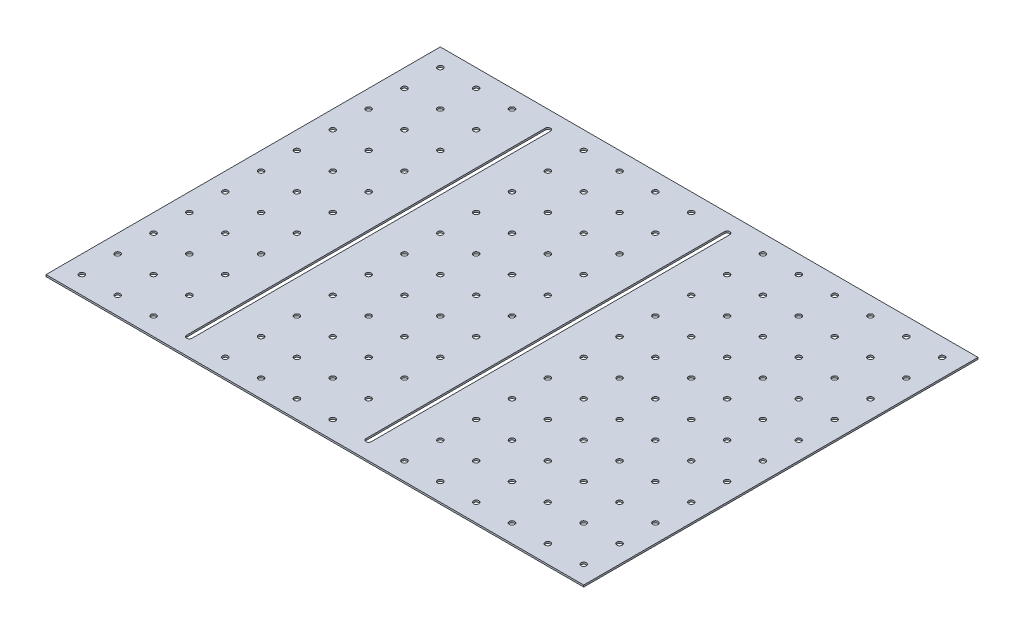
SolidWorks part; units mm, degrees
ref_plane "Front Plane" through (0, 0, 0) normal (0, 0, 1) x (1, 0, 0)
ref_plane "Top Plane" through (0, 0, 0) normal (0, 1, 0) x (1, 0, 0)
ref_plane "Right Plane" through (0, 0, 0) normal (1, 0, 0) x (0, 0, -1)
sketch "Sketch1" plane through (0, 0, 0) normal (0, 1, 0) x (1, 0, 0)
  line L1 (0, 0) -> (-300, 0)
  line L2 (0, 0) -> (0, 220)
  line L3 (0, 220) -> (-300, 220)
  line L4 (-300, 0) -> (-300, 220)
extrude "Boss-Extrude1" add sketch "Sketch1" along normal blind 1
sketch "Sketch2" plane through (0, 1, 0) normal (0, 1, 0) x (1, 0, 0)
  line L0 (-300, 220) -> (-300, 0) construction
  line L1 (0, 220) -> (-300, 220) construction
  line L2 (-280, 220) -> (-280, 0) construction
  line L3 (-300, 0) -> (0, 0) construction
  line L4 (-300, 200) -> (0, 200) construction
  line L5 (0, 0) -> (0, 220) construction
  line L6 (-280, 200) -> (-280, -20) construction
  line L7 (-280, 180) -> (-280, -40) construction
  line L8 (-280, 160) -> (-280, -60) construction
  line L9 (-280, 140) -> (-280, -80) construction
  line L10 (-280, 120) -> (-280, -100) construction
  line L11 (-280, 100) -> (-280, -120) construction
  line L12 (-280, 80) -> (-280, -140) construction
  line L13 (-280, 60) -> (-280, -160) construction
  line L14 (-280, 40) -> (-280, -180) construction
  line L15 (-280, 20) -> (-280, -200) construction
  circle A0 centre (-290, 210) radius 1.5
  circle A1 centre (-270, 210) radius 1.5
  circle A2 centre (-250, 210) radius 1.5
  circle A3 centre (-230, 210) radius 1.5
  circle A4 centre (-210, 210) radius 1.5
  circle A5 centre (-190, 210) radius 1.5
  circle A6 centre (-170, 210) radius 1.5
  circle A7 centre (-150, 210) radius 1.5
  circle A8 centre (-130, 210) radius 1.5
  circle A9 centre (-110, 210) radius 1.5
  circle A10 centre (-90, 210) radius 1.5
  circle A11 centre (-70, 210) radius 1.5
  circle A12 centre (-50, 210) radius 1.5
  circle A13 centre (-30, 210) radius 1.5
  circle A14 centre (-10, 210) radius 1.5
  circle A15 centre (-290, 190) radius 1.5
  circle A16 centre (-270, 190) radius 1.5
  circle A17 centre (-250, 190) radius 1.5
  circle A18 centre (-230, 190) radius 1.5
  circle A19 centre (-210, 190) radius 1.5
  circle A20 centre (-190, 190) radius 1.5
  circle A21 centre (-170, 190) radius 1.5
  circle A22 centre (-150, 190) radius 1.5
  circle A23 centre (-130, 190) radius 1.5
  circle A24 centre (-110, 190) radius 1.5
  circle A25 centre (-90, 190) radius 1.5
  circle A26 centre (-70, 190) radius 1.5
  circle A27 centre (-50, 190) radius 1.5
  circle A28 centre (-30, 190) radius 1.5
  circle A29 centre (-10, 190) radius 1.5
  circle A30 centre (-290, 170) radius 1.5
  circle A31 centre (-270, 170) radius 1.5
  circle A32 centre (-250, 170) radius 1.5
  circle A33 centre (-230, 170) radius 1.5
  circle A34 centre (-210, 170) radius 1.5
  circle A35 centre (-190, 170) radius 1.5
  circle A36 centre (-170, 170) radius 1.5
  circle A37 centre (-150, 170) radius 1.5
  circle A38 centre (-130, 170) radius 1.5
  circle A39 centre (-110, 170) radius 1.5
  circle A40 centre (-90, 170) radius 1.5
  circle A41 centre (-70, 170) radius 1.5
  circle A42 centre (-50, 170) radius 1.5
  circle A43 centre (-30, 170) radius 1.5
  circle A44 centre (-10, 170) radius 1.5
  circle A45 centre (-290, 150) radius 1.5
  circle A46 centre (-270, 150) radius 1.5
  circle A47 centre (-250, 150) radius 1.5
  circle A48 centre (-230, 150) radius 1.5
  circle A49 centre (-210, 150) radius 1.5
  circle A50 centre (-190, 150) radius 1.5
  circle A51 centre (-170, 150) radius 1.5
  circle A52 centre (-150, 150) radius 1.5
  circle A53 centre (-130, 150) radius 1.5
  circle A54 centre (-110, 150) radius 1.5
  circle A55 centre (-90, 150) radius 1.5
  circle A56 centre (-70, 150) radius 1.5
  circle A57 centre (-50, 150) radius 1.5
  circle A58 centre (-30, 150) radius 1.5
  circle A59 centre (-10, 150) radius 1.5
  circle A60 centre (-290, 130) radius 1.5
  circle A61 centre (-270, 130) radius 1.5
  circle A62 centre (-250, 130) radius 1.5
  circle A63 centre (-230, 130) radius 1.5
  circle A64 centre (-210, 130) radius 1.5
  circle A65 centre (-190, 130) radius 1.5
  circle A66 centre (-170, 130) radius 1.5
  circle A67 centre (-150, 130) radius 1.5
  circle A68 centre (-130, 130) radius 1.5
  circle A69 centre (-110, 130) radius 1.5
  circle A70 centre (-90, 130) radius 1.5
  circle A71 centre (-70, 130) radius 1.5
  circle A72 centre (-50, 130) radius 1.5
  circle A73 centre (-30, 130) radius 1.5
  circle A74 centre (-10, 130) radius 1.5
  circle A75 centre (-290, 110) radius 1.5
  circle A76 centre (-270, 110) radius 1.5
  circle A77 centre (-250, 110) radius 1.5
  circle A78 centre (-230, 110) radius 1.5
  circle A79 centre (-210, 110) radius 1.5
  circle A80 centre (-190, 110) radius 1.5
  circle A81 centre (-170, 110) radius 1.5
  circle A82 centre (-150, 110) radius 1.5
  circle A83 centre (-130, 110) radius 1.5
  circle A84 centre (-110, 110) radius 1.5
  circle A85 centre (-90, 110) radius 1.5
  circle A86 centre (-70, 110) radius 1.5
  circle A87 centre (-50, 110) radius 1.5
  circle A88 centre (-30, 110) radius 1.5
  circle A89 centre (-10, 110) radius 1.5
  circle A90 centre (-290, 90) radius 1.5
  circle A91 centre (-270, 90) radius 1.5
  circle A92 centre (-250, 90) radius 1.5
  circle A93 centre (-230, 90) radius 1.5
  circle A94 centre (-210, 90) radius 1.5
  circle A95 centre (-190, 90) radius 1.5
  circle A96 centre (-170, 90) radius 1.5
  circle A97 centre (-150, 90) radius 1.5
  circle A98 centre (-130, 90) radius 1.5
  circle A99 centre (-110, 90) radius 1.5
  circle A100 centre (-90, 90) radius 1.5
  circle A101 centre (-70, 90) radius 1.5
  circle A102 centre (-50, 90) radius 1.5
  circle A103 centre (-30, 90) radius 1.5
  circle A104 centre (-10, 90) radius 1.5
  circle A105 centre (-290, 70) radius 1.5
  circle A106 centre (-270, 70) radius 1.5
  circle A107 centre (-250, 70) radius 1.5
  circle A108 centre (-230, 70) radius 1.5
  circle A109 centre (-210, 70) radius 1.5
  circle A110 centre (-190, 70) radius 1.5
  circle A111 centre (-170, 70) radius 1.5
  circle A112 centre (-150, 70) radius 1.5
  circle A113 centre (-130, 70) radius 1.5
  circle A114 centre (-110, 70) radius 1.5
  circle A115 centre (-90, 70) radius 1.5
  circle A116 centre (-70, 70) radius 1.5
  circle A117 centre (-50, 70) radius 1.5
  circle A118 centre (-30, 70) radius 1.5
  circle A119 centre (-10, 70) radius 1.5
  circle A120 centre (-290, 50) radius 1.5
  circle A121 centre (-270, 50) radius 1.5
  circle A122 centre (-250, 50) radius 1.5
  circle A123 centre (-230, 50) radius 1.5
  circle A124 centre (-210, 50) radius 1.5
  circle A125 centre (-190, 50) radius 1.5
  circle A126 centre (-170, 50) radius 1.5
  circle A127 centre (-150, 50) radius 1.5
  circle A128 centre (-130, 50) radius 1.5
  circle A129 centre (-110, 50) radius 1.5
  circle A130 centre (-90, 50) radius 1.5
  circle A131 centre (-70, 50) radius 1.5
  circle A132 centre (-50, 50) radius 1.5
  circle A133 centre (-30, 50) radius 1.5
  circle A134 centre (-10, 50) radius 1.5
  circle A135 centre (-290, 30) radius 1.5
  circle A136 centre (-270, 30) radius 1.5
  circle A137 centre (-250, 30) radius 1.5
  circle A138 centre (-230, 30) radius 1.5
  circle A139 centre (-210, 30) radius 1.5
  circle A140 centre (-190, 30) radius 1.5
  circle A141 centre (-170, 30) radius 1.5
  circle A142 centre (-150, 30) radius 1.5
  circle A143 centre (-130, 30) radius 1.5
  circle A144 centre (-110, 30) radius 1.5
  circle A145 centre (-90, 30) radius 1.5
  circle A146 centre (-70, 30) radius 1.5
  circle A147 centre (-50, 30) radius 1.5
  circle A148 centre (-30, 30) radius 1.5
  circle A149 centre (-10, 30) radius 1.5
  circle A150 centre (-290, 10) radius 1.5
  circle A151 centre (-270, 10) radius 1.5
  circle A152 centre (-250, 10) radius 1.5
  circle A153 centre (-230, 10) radius 1.5
  circle A154 centre (-210, 10) radius 1.5
  circle A155 centre (-190, 10) radius 1.5
  circle A156 centre (-170, 10) radius 1.5
  circle A157 centre (-150, 10) radius 1.5
  circle A158 centre (-130, 10) radius 1.5
  circle A159 centre (-110, 10) radius 1.5
  circle A160 centre (-90, 10) radius 1.5
  circle A161 centre (-70, 10) radius 1.5
  circle A162 centre (-50, 10) radius 1.5
  circle A163 centre (-30, 10) radius 1.5
  circle A164 centre (-10, 10) radius 1.5
  dimension "D1" = 10
  dimension "D2" = 10
  dimension "D3" = 20
  dimension "D4" = 20
  dimension "D5" = 15
  dimension "D6" = 11
extrude "Cut-Extrude1" cut sketch "Sketch2" against normal blind 10
sketch "Sketch3" plane through (0, 1, 0) normal (0, 1, 0) x (1, 0, 0)
  line L0 (-231.5, 10) -> (-231.5, 210)
  line L1 (-228.5, 210) -> (-228.5, 10)
  circle A0 centre (-230, 10) radius 1.5 construction
  circle A1 centre (-230, 210) radius 1.5 construction
  arc A2 (-231.5, 10) -> (-228.5, 10) centre (-230, 10) ccw
  arc A3 (-228.5, 10) -> (-231.5, 10) centre (-230, 10) cw
  arc A4 (-228.5, 210) -> (-231.5, 210) centre (-230, 210) ccw
extrude "Cut-Extrude2" cut sketch "Sketch3" against normal up to next contours L1 A4 L0 A2
sketch "Sketch4" plane through (0, 1, 0) normal (0, 1, 0) x (1, 0, 0)
  line L0 (-131.5, 10) -> (-131.5, 210)
  line L1 (-128.5, 10) -> (-128.5, 210)
  circle A0 centre (-130, 10) radius 1.5 construction
  circle A1 centre (-130, 210) radius 1.5 construction
  arc A2 (-128.5, 10) -> (-131.5, 10) centre (-130, 10) cw
  arc A3 (-128.5, 210) -> (-131.5, 210) centre (-130, 210) ccw
extrude "Cut-Extrude3" cut sketch "Sketch4" against normal up to next
